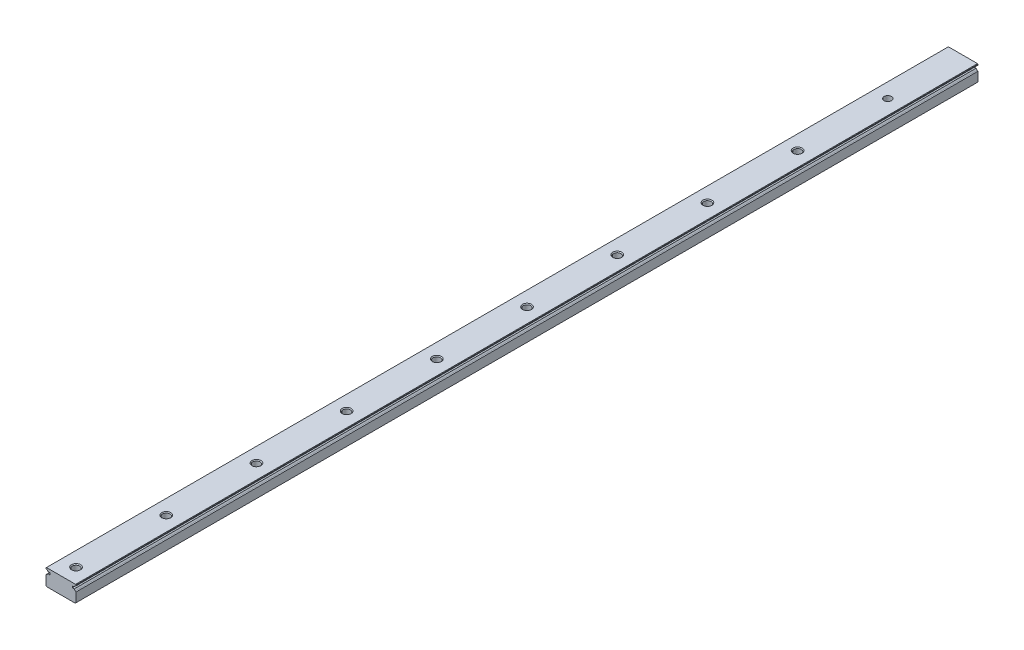
SolidWorks part; units mm, degrees
ref_plane "Plan de face" through (0, 0, 0) normal (0, 0, 1) x (1, 0, 0)
ref_plane "Plan de dessus" through (0, 0, 0) normal (0, 1, 0) x (1, 0, 0)
ref_plane "Plan de droite" through (0, 0, 0) normal (1, 0, 0) x (0, 0, -1)
ref_plane "Plan1" through (0, 0, 0) normal (0, -1, 0) x (1, 0, 0)
sketch "Esquisse1" plane through (0, 0, 0) normal (0, -1, 0) x (1, 0, 0)
  line L0 (-10, -350) -> (10, -350)
  line L1 (10, -350) -> (10, 250)
  line L2 (10, 250) -> (-10, 250)
  line L3 (-10, 250) -> (-10, -350)
  dimension "D1" = 600
  dimension "D2" = 20
extrude "Boss.-Extru.1" add sketch "Esquisse1" against normal blind 11
sketch "Esquisse2" plane through (0, 0, -350) normal (0, 0, -1) x (-1, 0, 0)
  line L0 (10, 7.9) -> (10, 10.2238)
  line L1 (10, 10.2238) -> (9.44, 9.9006)
  line L2 (8.7177, 9.1) -> (7.5, 9.1)
  line L3 (7.5, 9.1) -> (7.5, 7.9)
  line L4 (7.5, 7.9) -> (10, 7.9)
  arc A0 (9.44, 9.9006) -> (8.7177, 9.1) centre (10.315, 8.385) ccw
extrude "Enlèv. mat.-Extru.1" cut sketch "Esquisse2" against normal through all
sketch "Esquisse3" plane through (0, 0, -350) normal (0, 0, -1) x (-1, 0, 0)
  line L0 (9.44, 7.0994) -> (10, 6.7761)
  line L1 (10, 6.7761) -> (10, 7.9)
  line L2 (10, 7.9) -> (8.7177, 7.9)
  arc A0 (8.7177, 7.9) -> (9.44, 7.0994) centre (10.315, 8.615) ccw
extrude "Enlèv. mat.-Extru.2" cut sketch "Esquisse3" against normal through all
sketch "Esquisse4" plane through (0, 0, -350) normal (0, 0, -1) x (-1, 0, 0)
  line L0 (-10, 9.1) -> (-10, 6.7761)
  line L1 (-10, 6.7761) -> (-9.44, 7.0994)
  line L2 (-8.7177, 7.9) -> (-7.5, 7.9)
  line L3 (-7.5, 7.9) -> (-7.5, 9.1)
  line L4 (-7.5, 9.1) -> (-10, 9.1)
  arc A0 (-9.44, 7.0994) -> (-8.7177, 7.9) centre (-10.315, 8.615) ccw
extrude "Enlèv. mat.-Extru.3" cut sketch "Esquisse4" against normal through all
sketch "Esquisse5" plane through (0, 0, -350) normal (0, 0, -1) x (-1, 0, 0)
  line L0 (-9.44, 9.9006) -> (-10, 10.2239)
  line L1 (-10, 10.2239) -> (-10, 9.1)
  line L2 (-10, 9.1) -> (-8.7177, 9.1)
  arc A0 (-8.7177, 9.1) -> (-9.44, 9.9006) centre (-10.315, 8.385) ccw
extrude "Enlèv. mat.-Extru.4" cut sketch "Esquisse5" against normal through all
hole_wizard "Perçage1" positions "Esquisse7" profile "Esquisse6" legacy
sketch "Esquisse7" plane through (0, 11, 0) normal (0, 1, 0) x (1, 0, 0)
  point P0 (0, -180)
  point P1 (0, -120)
  point P2 (0, 60)
  point P3 (0, 180)
sketch "Esquisse6" plane through (0, 11, 180) normal (1, 0, 0) x (0, 0, 1)
  line L0 (0, 0) -> (0, 11)
  line L1 (0, 11) -> (2.4585, 11)
  line L2 (2.4585, 11) -> (2.4585, 0)
  line L3 (2.4585, 0) -> (0, 0)
  line L4 (0, 110) -> (0, -10) construction
  dimension "Diamètre" = 4.917
  dimension "Profondeur" = 11
hole_wizard "Perçage2" positions "Esquisse9" profile "Esquisse8" legacy end condition through all
sketch "Esquisse9" plane through (0, 0, 0) normal (0, -1, 0) x (-1, 0, 0)
  point P0 (0, -240)
  point P1 (0, -60)
  point P2 (0, 0)
  point P3 (0, 120)
  point P4 (0, 240)
sketch "Esquisse8" plane through (0, 0, 240) normal (1, 0, 0) x (0, 0, -1)
  line L0 (0, 0) -> (0, 11)
  line L1 (0, 11) -> (2.4585, 11)
  line L2 (2.4585, 11) -> (2.4585, 0)
  line L3 (2.4585, 0) -> (0, 0)
  line L4 (0, 110) -> (0, -10) construction
  dimension "Diamètre" = 4.917
  dimension "Profondeur" = 11
chamfer "Chanfrein1" distance 0.5415 angle 45 20 edges at (0, 11, -242.4585) (0, 11, -2.4585) (0, 0, -2.4585) (0, 0, -57.5415) (0, 11, -122.4585) (0, 0, -122.4585) (0, 0, -177.5415) (0, 11, 57.5415) (0, 0, -242.4585) (0, 11, -57.5415) (-10, 0, -50) (0, 11, -177.5415) (10, 0, -50) (0, 0, 182.4585) (0, 0, 57.5415) (0, 0, 122.4585) (0, 11, 122.4585) (0, 11, 237.5415) (0, 0, 237.5415) (0, 11, 182.4585)
chamfer "Chanfrein2" distance 0.3 angle 45 2 edges at (-10, 11, -50) (10, 11, -50)
pattern_linear "Répétition linéaire1" count 9 spacing 60 along (0, 0, -1) of "Perçage2"
